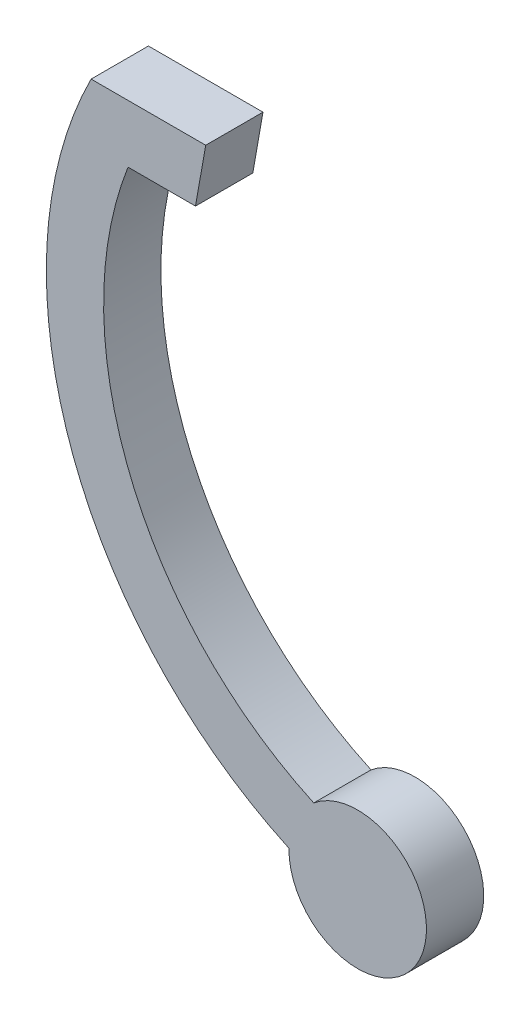
SolidWorks part; units mm, degrees
ref_plane "Front Plane" through (0, 0, 0) normal (0, 0, 1) x (1, 0, 0)
ref_plane "Top Plane" through (0, 0, 0) normal (0, 1, 0) x (1, 0, 0)
ref_plane "Right Plane" through (0, 0, 0) normal (1, 0, 0) x (0, 0, -1)
sketch "Esquisse1" plane through (0, 0, 0) normal (0, 0, 1) x (1, 0, 0)
  line L0 (15.3093, -19.0875) -> (10.9159, -19.0875)
  line L1 (10.9159, -19.0875) -> (10.7066, -15.093)
  line L2 (10.7066, -15.093) -> (12.7066, -15.093)
  line L5 (12.7605, -16.069) -> (12.7605, -16.069)
  line L6 (10.7066, -15.093) -> (11.0148, -15.093) construction
  line L8 (13.088, -17.0875) -> (12.8139, -17.0875) construction
  line L9 (12.8139, -17.0875) -> (12.7605, -16.069) construction
  arc A0 (5.5869, -2.1879) -> (4.5574, -3.9026) centre (0, 0) ccw
  arc A1 (5.5869, -2.1879) -> (4.5574, -3.9026) centre (0, 0) cw
  spline S0 degree 2 poles (5.5869, -2.1879) (14.5406, -7.5636) (15.3093, -19.0875) knots 0 0 0 1 1 1
  spline S1 degree 1 poles (4.5574, -3.9026) (13.088, -17.0875) knots 0 0 1 1 construction
  spline S2 degree 3 poles (4.5574, -3.9026) (5.1538, -4.2606) (6.3293, -5.0512) (7.8474, -6.3386) (9.1825, -7.7619) (10.3283, -9.3178) (11.2946, -11.0173) (12.073, -12.845) (12.5249, -14.3273) (12.776, -15.3824) (12.9325, -16.1265) (13.0332, -16.7159) (13.088, -17.0875) knots 0 0 0 0 0.112224 0.224447 0.336671 0.448894 0.561118 0.673342 0.781406 0.809462 0.841677 0.897789 0.897789 0.897789 0.897789 only from (4.5574, -3.9026) to (12.702, -15.0739)
  dimension "D1" = 12
  dimension "D2" = 4
  dimension "D3" = 2
  dimension "D5" = 93
  dimension "D4" = 2
extrude "Boss.-Extru.2" add sketch "Esquisse1" along normal blind 5 contours A1 A0
sketch "Esquisse7" plane through (0, 0, 0) normal (0, 0, -1) x (-1, 0, 0)
  line L0 (23.2674, 49.6141) -> (13.2674, 49.6141)
  line L1 (13.2674, 49.6141) -> (14.1574, 44.5667)
  line L2 (14.1574, 44.5667) -> (20.0475, 44.5667)
  arc A0 (5.9991, 0.1058) -> (23.2674, 49.6141) centre (-9.263, 33.1948) ccw
  circle A1 centre (0, 0) radius 6 construction
  arc A2 (20.0475, 44.5667) -> (3.8353, 4.6141) centre (-9.263, 33.1948) cw
  circle A4 centre (0, 0) radius 6
  arc A5 (5.9991, 0.1058) -> (3.8353, 4.6141) centre (0, 0) ccw
  dimension "D5" = 5
  dimension "D1" = 80
  dimension "D2" = 10
  dimension "D3" = 45
  dimension "D4" = 0
extrude "Boss.-Extru.8" add sketch "Esquisse7" along normal mid plane 10 from offset 1 offset against normal yes
sketch "Esquisse8" plane through (0, 0, 0) normal (0, 1, 0) x (1, 0, 0)
  line L2 (-31.0252, 0) -> (-31.0252, -5)
  line L3 (-31.0252, 0) -> (-4.4763, 0)
  line L4 (-31.0252, -5) -> (-4.4763, -5)
  line L5 (-4.4763, 0) -> (6.1856, 0)
  line L6 (6.1856, 0) -> (6.1856, -5)
  line L7 (6.1856, -5) -> (-4.4763, -5)
  dimension "D1" = 5
  dimension "D2" = 5
extrude "Enlèv. mat.-Extru.3" cut sketch "Esquisse8" against normal through all and the other way through all flip side to cut
sketch "Esquisse9" plane through (0, 49.6141, 0) normal (0, 1, 0) x (1, 0, 0)
  line L0 (-13.2674, 0) -> (-13.2674, -5) construction
  line L1 (-13.2674, 0) -> (-13.2674, -5)
  arc A1 (-13.2674, 0) -> (-13.2674, -1.9411) centre (-26.5363, -0.9706) cw
extrude "Boss.-Extru.9" [suppressed] add sketch "Esquisse9" against normal up to surface (4 mm away) contours A1 L1
